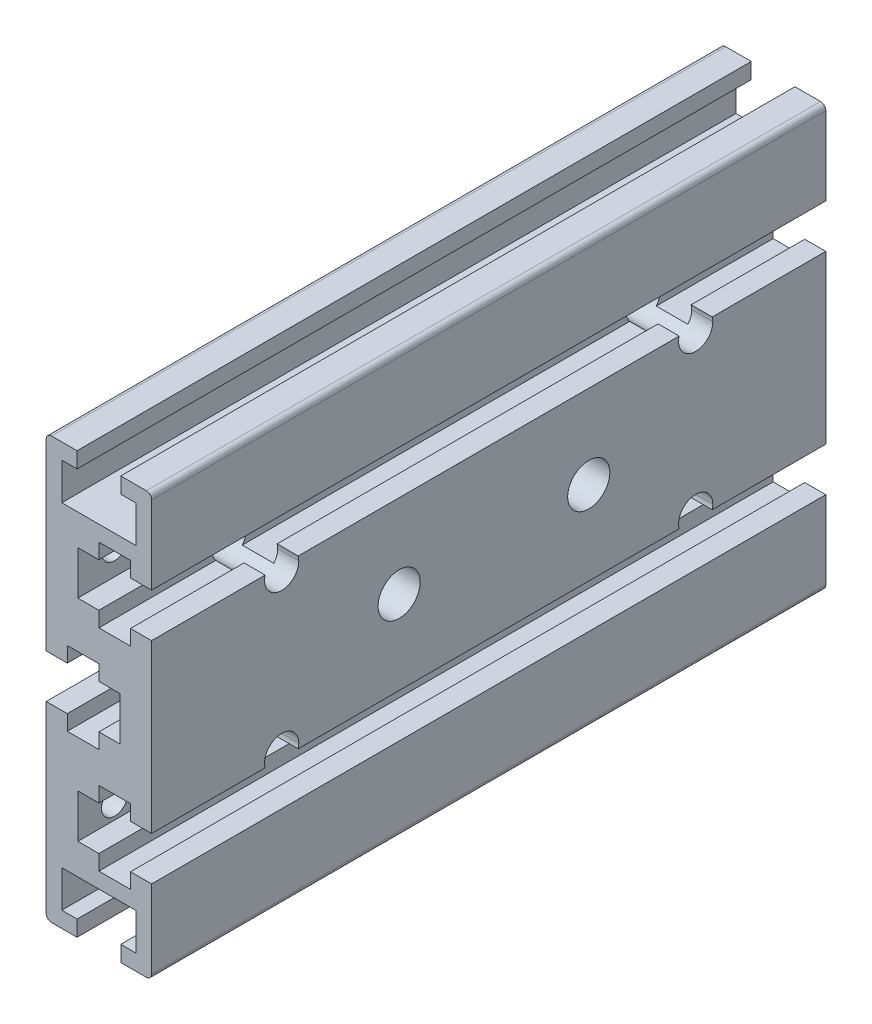
SolidWorks part; units mm, degrees
ref_plane "Plane1" through (0, 0, 0) normal (0, 0, 1) x (1, 0, 0)
ref_plane "Plane2" through (0, 0, 0) normal (0, 1, 0) x (1, 0, 0)
ref_plane "Plane3" through (0, 0, 0) normal (1, 0, 0) x (0, 0, -1)
sketch "Sketch1" plane through (0, 0, 0) normal (0, 0, 1) x (1, 0, 0)
  line L0 (0, 0) -> (75.649, 0) construction
  line L1 (-9, 40) -> (-4.15, 40)
  line L2 (-10, 39) -> (-10, 4.15)
  line L3 (-9, -40) -> (-4.15, -40)
  line L4 (10, 39) -> (10, 24.15)
  line L5 (0, 3.6903) -> (0, 44.6054) construction
  line L6 (-4.15, 40) -> (-4.15, 37)
  line L7 (-4.15, 37) -> (-7.05, 37)
  line L8 (-7.05, 37) -> (-7.05, 30)
  line L9 (-7.05, 30) -> (7.05, 30)
  line L10 (7.05, 30) -> (7.05, 37)
  line L11 (7.05, 37) -> (4.15, 37)
  line L12 (4.15, 37) -> (4.15, 40)
  line L13 (4.15, 40) -> (9, 40)
  line L14 (4.15, -37) -> (4.15, -40)
  line L15 (7.05, -37) -> (4.15, -37)
  line L16 (7.05, -30) -> (7.05, -37)
  line L17 (-7.05, -30) -> (7.05, -30)
  line L18 (-7.05, -37) -> (-7.05, -30)
  line L19 (-4.15, -37) -> (-7.05, -37)
  line L20 (-4.15, -40) -> (-4.15, -37)
  line L21 (4.15, -40) -> (9, -40)
  line L22 (-6, -7.05) -> (0, -7.05)
  line L23 (-10, -4.15) -> (-6, -4.15)
  line L24 (-6, 4.15) -> (-10, 4.15)
  line L25 (0, -7.05) -> (0, -4.15)
  line L26 (-6, -4.15) -> (-6, -7.05)
  line L27 (0, 7.05) -> (-6, 7.05)
  line L28 (-17.4711, 20) -> (26.2798, 20) construction
  line L29 (-6, 7.05) -> (-6, 4.15)
  line L30 (-17.4711, -20) -> (26.2798, -20) construction
  line L31 (-4, -15.85) -> (-4, -24.15)
  line L32 (0, -27.05) -> (0, -24.15)
  line L33 (6, -15.85) -> (10, -15.85)
  line L34 (6, -24.15) -> (6, -27.05)
  line L35 (0, -15.85) -> (0, -12.95)
  line L36 (0, 4.15) -> (4, 4.15)
  line L37 (4, 4.15) -> (4, -4.15)
  line L38 (4, -4.15) -> (0, -4.15)
  line L39 (0, 4.15) -> (0, 7.05)
  line L40 (-10, -4.15) -> (-10, -39)
  line L41 (6, 12.95) -> (6, 15.85)
  line L42 (6, 27.05) -> (0, 27.05)
  line L43 (0, 12.95) -> (6, 12.95)
  line L44 (-4, 24.15) -> (0, 24.15)
  line L45 (10, 24.15) -> (6, 24.15)
  line L46 (0, 15.85) -> (-4, 15.85)
  line L47 (0, 15.85) -> (0, 12.95)
  line L48 (6, 24.15) -> (6, 27.05)
  line L49 (0, -15.85) -> (-4, -15.85)
  line L50 (6, 15.85) -> (10, 15.85)
  line L51 (0, 27.05) -> (0, 24.15)
  line L52 (10, -24.15) -> (6, -24.15)
  line L53 (-4, 15.85) -> (-4, 24.15)
  line L54 (-4, -24.15) -> (0, -24.15)
  line L55 (0, -12.95) -> (6, -12.95)
  line L56 (6, -27.05) -> (0, -27.05)
  line L57 (6, -12.95) -> (6, -15.85)
  line L58 (10, 15.85) -> (10, -15.85)
  line L59 (10, -24.15) -> (10, -39)
  arc A0 (9, -40) -> (10, -39) centre (9, -39) ccw
  arc A1 (-10, -39) -> (-9, -40) centre (-9, -39) ccw
  arc A2 (-9, 40) -> (-10, 39) centre (-9, 39) ccw
  arc A3 (9, 40) -> (10, 39) centre (9, 39) cw
  point P72 (-10, 40)
  point P73 (10, 40)
  point P74 (0, 40)
  point P75 (-10, -40)
  point P76 (10, -40)
  point P77 (0, -40)
  point P78 (10, -20)
  point P79 (-10, 0)
  point P80 (10, 20)
  point P81 (-10, 20)
  point P82 (10, 0)
  point P83 (-10, -20)
extrude "凸台-拉伸1" add sketch "Sketch1" along normal blind 128
hole_wizard "Ø5.0 (5) 直径孔1" positions "草图2" profile "草图1" hole size "Ø5.0" standard "Gb" end condition through all
sketch "草图2" plane through (-4, 0, 0) normal (1, 0, 0) x (0, 0, -1)
  line L0 (-128, 40) -> (0, 40) construction
  line L1 (-128, -40) -> (0, -40) construction
  line L2 (-128, 24.15) -> (-128, 39) construction
  line L3 (-128, -24.15) -> (-128, -15.85) construction
  line L4 (-128, -15.85) -> (-128, 15.85) construction
  point P0 (-121, 21)
  point P2 (-97, 21)
  point P4 (-31, 21)
  point P6 (-7, 21)
  point P8 (-7, -21)
  point P10 (-31, -21)
  point P12 (-97, -21)
  point P14 (-121, -21)
  dimension "D1" = 19
  dimension "D2" = 19
  dimension "D3" = 7
  dimension "D4" = 31
  dimension "D5" = 97
  dimension "D6" = 121
sketch "草图1" plane through (-4, 21, 121) normal (0, 1, 0) x (0, 0, -1)
  line L0 (0, 0) -> (0, 6)
  line L1 (0, 6) -> (2.5, 6)
  line L2 (2.5, 6) -> (2.5, 0)
  line L5 (2.5, 0) -> (0, 0)
  line L11 (0, -6.35) -> (0, 107.95) construction
  dimension "通孔孔直径" = 5
  dimension "通孔孔深度" = 6
hole_wizard "Ø6.5 (6.5) 直径孔1_电机底座" positions "草图4" profile "草图3" hole size "Ø6.5" standard "Gb" end condition through all
sketch "草图4" plane through (10, 0, 0) normal (1, 0, 0) x (0, 0, -1)
  line L0 (-128, -15.85) -> (-128, 15.85) construction
  line L1 (0, -15.85) -> (0, 15.85) construction
  line L3 (-128, 40) -> (0, 40) construction
  point P0 (-103.3, 15)
  point P2 (-24.7, 15)
  point P4 (-24.7, -15)
  point P6 (-103.3, -15)
  point P20 (-112.6938, -0.4006)
  dimension "D1" = 24.7
  dimension "D2" = 24.7
  dimension "D3" = 30
  dimension "D4" = 25
sketch "草图3" plane through (10, 15, 103.3) normal (0, 1, 0) x (0, 0, -1)
  line L0 (0, 0) -> (0, 20)
  line L1 (0, 20) -> (3.25, 20)
  line L2 (3.25, 20) -> (3.25, 0)
  line L5 (3.25, 0) -> (0, 0)
  line L11 (0, -6.35) -> (0, 107.95) construction
  dimension "通孔孔直径" = 6.5
  dimension "通孔孔深度" = 20
hole_wizard "Ø8.0 (8) 直径孔1" positions "草图6" profile "草图5" hole size "Ø8.0" standard "Gb" end condition through all
sketch "草图6" plane through (10, 0, 0) normal (1, 0, 0) x (0, 0, -1)
  line L0 (-128, -15.85) -> (-128, 15.85) construction
  line L4 (-128, -40) -> (0, -40) construction
  point P0 (-81, 0)
  point P2 (-45, 0)
  point P11 (-80.5328, 40)
  dimension "D1" = 47
  dimension "D2" = 40
  dimension "D3" = 83
sketch "草图5" plane through (10, 0, 81) normal (0, 1, 0) x (0, 0, -1)
  line L0 (0, 0) -> (0, 20)
  line L1 (0, 20) -> (4, 20)
  line L2 (4, 20) -> (4, 0)
  line L5 (4, 0) -> (0, 0)
  line L11 (0, -6.35) -> (0, 107.95) construction
  dimension "通孔孔直径" = 8
  dimension "通孔孔深度" = 20
